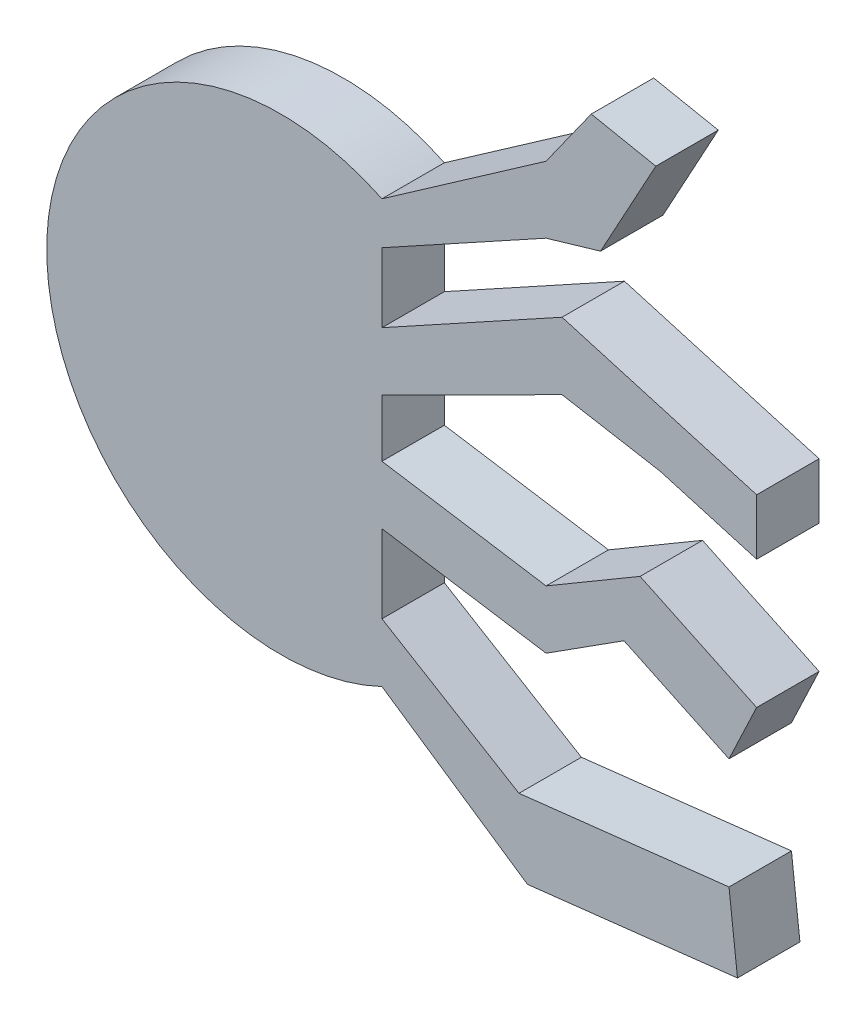
SolidWorks part; units mm, degrees
ref_plane "Front Plane" through (0, 0, 0) normal (1, 0, 0) x (0, 1, 0)
ref_plane "Top Plane" through (0, 0, 0) normal (0, 0, 1) x (0, 1, 0)
ref_plane "Right Plane" through (0, 0, 0) normal (0, 1, 0) x (-1, 0, 0)
sketch "Sketch1" plane through (0, 0, 0) normal (0, 0, 1) x (0, 1, 0)
  line L0 (16.2236, -9.7132) -> (9.5695, -9.7132)
  line L1 (-20.2954, -9.7132) -> (-29.7646, -23.6967)
  line L2 (-29.7646, -23.6967) -> (-27.4652, -43.8804)
  line L3 (-27.4652, -43.8804) -> (-20.2954, -43.0636)
  line L4 (-20.2954, -43.0636) -> (-22.5948, -22.8799)
  line L5 (-7.1537, -9.7132) -> (-14.6563, -9.7132)
  line L6 (36.1714, -36.0307) -> (37.4049, -29.8242)
  line L7 (-7.1537, -9.7132) -> (-9.6375, -25.4851)
  line L8 (-9.6375, -25.4851) -> (-4.8543, -32.9717)
  line L9 (-4.8543, -32.9717) -> (-9.6375, -43.0636)
  line L10 (-9.6375, -43.0636) -> (-4.0318, -45.7205)
  line L11 (-4.0318, -45.7205) -> (1.2771, -34.5194)
  line L12 (1.2771, -34.5194) -> (-4.0318, -25.4851)
  line L13 (-4.0318, -25.4851) -> (-1.548, -9.7132)
  line L14 (3.9601, -9.7132) -> (12.6468, -27.0181)
  line L15 (12.6468, -27.0181) -> (10.9861, -36.4712)
  line L16 (10.9861, -36.4712) -> (8.3034, -45.7205)
  line L17 (8.3034, -45.7205) -> (13.6687, -45.7205)
  line L18 (13.6687, -45.7205) -> (19.0931, -27.0181)
  line L19 (19.0931, -27.0181) -> (9.5695, -9.7132)
  line L20 (16.2236, -9.7132) -> (24.9036, -25.4851)
  line L21 (24.9036, -25.4851) -> (26.4432, -30.7227)
  line L22 (26.4432, -30.7227) -> (36.1714, -36.0307)
  line L26 (37.4049, -29.8242) -> (31.3073, -25.4851)
  line L27 (31.3073, -25.4851) -> (20.2954, -9.7132)
  line L28 (3.9601, -9.7132) -> (-1.548, -9.7132)
  line L29 (-22.5948, -22.8799) -> (-14.6563, -9.7132)
  arc A2 (20.2954, -9.7132) -> (-20.2954, -9.7132) centre (0, 0) ccw
extrude "Boss-Extrude1" add sketch "Sketch1" along normal blind 6
sketch "Sketch2" plane through (0, 0, 0) normal (0, 0, -1) x (1, 0, 0)
  circle A0 centre (0, 0) radius 5
  dimension "D1" = 10
extrude "Cut-Extrude1" cut sketch "Sketch2" against normal blind 3
